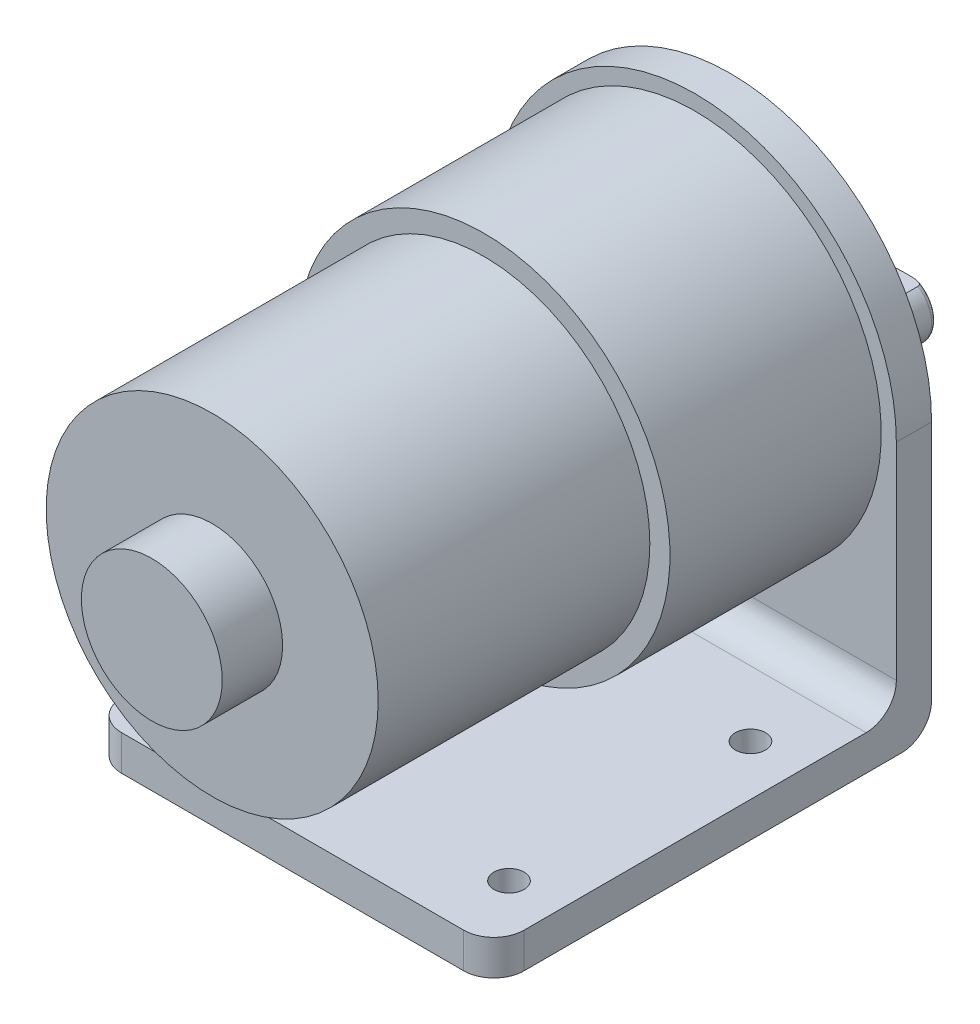
SolidWorks part; units mm, degrees
ref_plane "Front Plane" through (0, 0, 0) normal (0, 0, 1) x (1, 0, 0)
ref_plane "Top Plane" through (0, 0, 0) normal (0, 1, 0) x (1, 0, 0)
ref_plane "Right Plane" through (0, 0, 0) normal (1, 0, 0) x (0, 0, -1)
sketch "Sketch1" plane through (0, 0, 0) normal (0, 0, 1) x (1, 0, 0)
  circle A0 centre (0, 0) radius 18.5
  dimension "D1" = 37
extrude "Boss-Extrude1" add sketch "Sketch1" along normal blind 21
sketch "Sketch2" plane through (0, 0, 21) normal (0, 0, 1) x (1, 0, 0)
  circle A0 centre (0, 0) radius 16.5
  dimension "D1" = 33
extrude "Boss-Extrude2" add sketch "Sketch2" along normal blind 27
sketch "Sketch3" plane through (0, 0, 48) normal (0, 0, 1) x (1, 0, 0)
  circle A0 centre (0, 0) radius 7
  dimension "D1" = 14
extrude "Boss-Extrude3" add sketch "Sketch3" along normal blind 6
sketch "Sketch4" plane through (0, 0, 0) normal (0, 0, -1) x (-1, 0, 0)
  line L0 (-49.374, -27) -> (58.383, -27) construction
  line L1 (-20, 0) -> (-20, -27)
  line L2 (20, 0) -> (20, -27)
  line L3 (20, -27) -> (-20, -27)
  line L4 (0, 27.963) -> (0, -32.292) construction
  line L5 (0, 5) -> (0, -8.5) construction
  line L6 (6.5, 5) -> (6.5, -8.5)
  line L7 (-6.5, 5) -> (-6.5, -8.5)
  arc A0 (20, 0) -> (-20, 0) centre (0, 0) ccw
  arc A1 (-20, 0) -> (20, 0) centre (0, 0) ccw construction
  arc A2 (6.5, 5) -> (-6.5, 5) centre (0, 5) ccw
  arc A3 (-6.5, -8.5) -> (6.5, -8.5) centre (0, -8.5) ccw
  point P12 (0, -1.75)
  dimension "D1" = 40
  dimension "D3" = 13
  dimension "D2" = 27
  dimension "D4" = 32
  dimension "D5" = 18.5
extrude "Boss-Extrude4" add sketch "Sketch4" along normal blind 3.5
sketch "Sketch5" plane through (0, 0, 0) normal (0, 0, 1) x (1, 0, 0)
  line L0 (20, -27) -> (-20, -27) construction
  line L1 (20, -27) -> (-20, -27)
  line L2 (-20, -27) -> (-20, -23.5)
  line L3 (-20, -27) -> (-20, 0) construction
  line L4 (-20, -23.5) -> (20, -23.5)
  line L5 (20, 0) -> (20, -27) construction
  line L6 (20, -23.5) -> (20, -27)
  dimension "D1" = 3.5
extrude "Boss-Extrude5" add sketch "Sketch5" along normal blind 40
fillet "Fillet1" radius 3 4 edges at (0, -27, -3.5) (0, -23.5, 0) (-20, -25.25, 40) (20, -25.25, 40)
sketch "Sketch6" plane through (0, 0, 0) normal (0, 0, -1) x (-1, 0, 0)
  arc A1 (-6.5, -8.5) -> (6.5, -8.5) centre (0, -8.5) ccw construction
  circle A2 centre (0, -8.5) radius 6
  arc A3 (-6.5, -8.5) -> (6.5, -8.5) centre (0, -8.5) ccw construction
  dimension "D1" = 12
extrude "Boss-Extrude6" add sketch "Sketch6" along normal blind 6
sketch "Sketch7" plane through (0, 0, -6) normal (0, 0, -1) x (-1, 0, 0)
  circle A0 centre (0, -8.5) radius 6 construction
  circle A1 centre (0, -8.5) radius 6 construction
  circle A2 centre (0, -8.5) radius 3
  dimension "D1" = 6
extrude "Boss-Extrude7" add sketch "Sketch7" along normal blind 15
fillet "Fillet2" radius 0.5 1 edges at (-3, -8.5, -21)
sketch "Sketch8" plane through (0, 0, -21) normal (0, 0, -1) x (-1, 0, 0)
  line L0 (-1.6583, -6) -> (1.6583, -6)
  circle A0 centre (0, -8.5) radius 3 construction
  arc A1 (1.6583, -6) -> (-1.6583, -6) centre (0, -8.5) ccw
  arc A2 (-1.6583, -6) -> (1.6583, -6) centre (0, -8.5) ccw construction
  dimension "D1" = 2.5
extrude "Cut-Extrude1" cut sketch "Sketch8" against normal blind 12
sketch "Sketch9" plane through (0, -27, 0) normal (0, -1, 0) x (1, 0, 0)
  line L0 (0, 0) -> (0, 74.3316) construction
  line L1 (-17, 40) -> (17, 40) construction
  line L2 (-17, 40) -> (17, 40) construction
  line L3 (15, 40) -> (15, 4.9666) construction
  circle A0 centre (15, 33.5) radius 1.5
  circle A1 centre (15, 9.5) radius 1.5
  circle A2 centre (-15, 33.5) radius 1.5
  circle A3 centre (-15, 9.5) radius 1.5
  dimension "D2" = 3
  dimension "D1" = 15
  dimension "D3" = 6.5
  dimension "D4" = 30.5
extrude "Cut-Extrude2" cut sketch "Sketch9" against normal up to next
